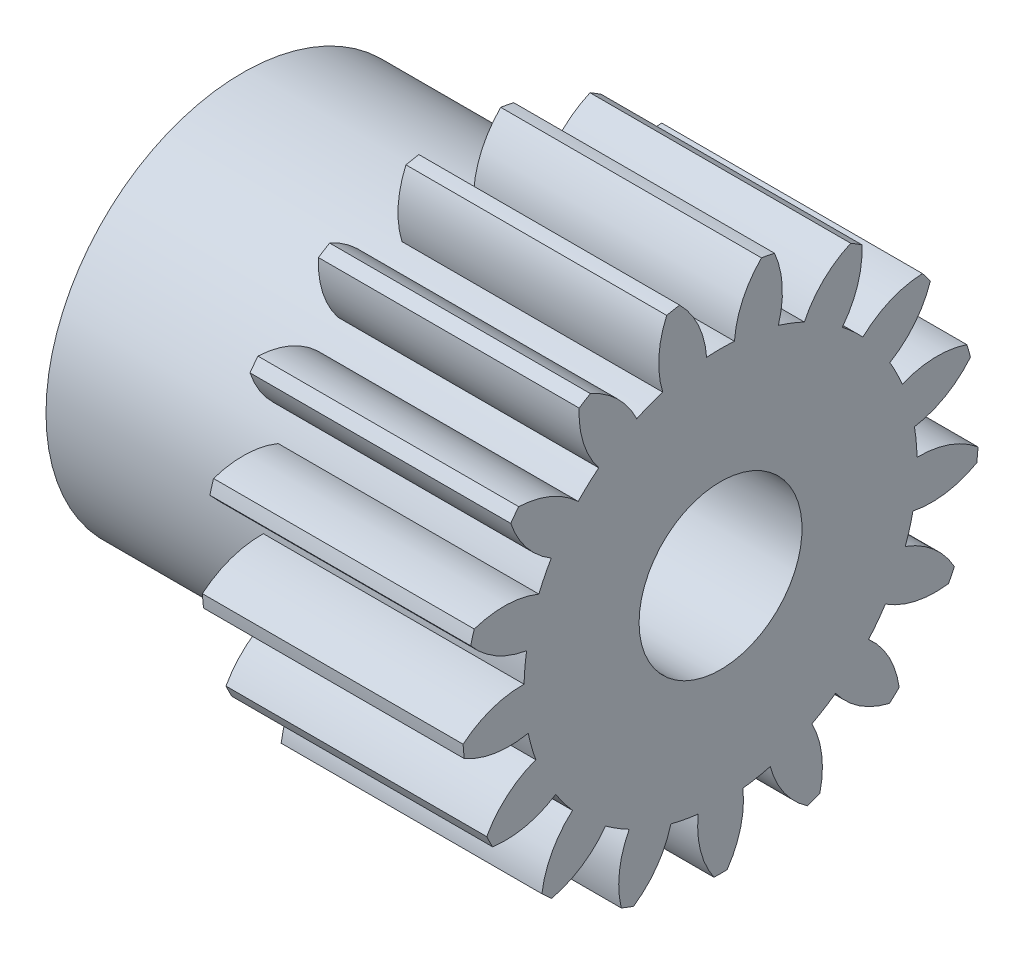
SolidWorks part; units mm, degrees
ref_plane "Plane1" through (0, 0, 0) normal (0, 0, 1) x (1, 0, 0)
ref_plane "Plane2" through (0, 0, 0) normal (0, 1, 0) x (1, 0, 0)
ref_plane "Plane3" through (0, 0, 0) normal (1, 0, 0) x (0, 0, -1)
sketch "HoldingSke" plane through (0, 0, 0) normal (0, 1, 0) x (1, 0, 0)
  line L0 (0, 0) -> (777.2845, -237.6397)
  line L1 (-15, 0) -> (100, 0) construction
  line L2 (0, 0) -> (-2.1039, 2.3779)
  line L3 (0, 0) -> (-11.863, 4.5341)
  line L4 (0, 0) -> (8.2586, 2.5249)
  line L5 (0, 0) -> (-13.0892, -4.8819)
  line L6 (0, 0) -> (-6.3167, -4.2619)
  line L7 (-2.1039, 2.3779) -> (0.9032, 16.0205)
  line L8 (-76.2, 54.61) -> (-71.1708, 54.61)
  line L9 (-71.009, 38.7566) -> (-53.1078, 45.2721)
  line L10 (-76.2, 71.12) -> (104.1128, 71.12)
  line L11 (0, 0) -> (-7.62, 0)
  line L12 (-76.2, 101.6) -> (-76.1716, 101.6)
  line L13 (24.9733, 27.94) -> (52.9518, 28.4284)
  line L14 (24.9733, 27.94) -> (25.0241, 27.9398)
  line L15 (24.9733, 27.94) -> (100.4021, 29.52)
  circle A0 centre (0, 0) radius 2.3813
  circle A1 centre (0, 0) radius 5.7436
  circle A2 centre (0, 0) radius 5.969
  circle A3 centre (0, 0) radius 2.3813
  dimension "MHD" = 11.4871
  dimension "Hub_dia" = 11.938
  dimension "Bore" = 4.7625
  dimension "MBD" = 4.7625
  dimension "Num_teeth" = 17
  dimension "Pitch" = 812.8
  dimension "Overall_len" = 13.97
  dimension "Show_teeth" = 17
  dimension "Thickness" = 7.62
  dimension "OAL" = 13.9701
  dimension "T_dim" = 5.0292
  dimension "Ap" = 20
  dimension "H" = 19.05
  dimension "Pitch_radius" = 180.3128
  dimension "Width" = 7.62
  dimension "Backlash" = 0.0284
  dimension "Addendum_fac" = 1
  dimension "Dedendum_fac" = 1.2
  dimension "Clearance_fac" = 0.2
  dimension "Dedendum_add" = 0.0508
sketch "BasProSke" plane through (0, 0, 0) normal (0, 1, 0) x (1, 0, 0)
  line L0 (-10, 0) -> (60, 0) construction
  line L1 (0, 0) -> (0, 7.5406)
  line L2 (0, 0) -> (7.62, 0)
  line L3 (7.62, 0) -> (7.62, 7.5406)
  line L4 (7.62, 7.5406) -> (0, 7.5406)
  dimension "Thickness" = 7.62
  dimension "Diameter" = 15.0812
revolve "Base-Revolve" add sketch "BasProSke" angle 360 about L0
sketch "TooCutSke" plane through (0, 0, 0) normal (1, 0, 0) x (0, 0, -1)
  line L1 (0, 0) -> (0, 107) construction
  line L2 (0, 0) -> (-0.6723, 6.7133) construction
  line L3 (0, 0) -> (-2.4705, 13.2161) construction
  line L4 (-0.6723, 6.7133) -> (-1.2353, 6.6081) construction
  arc A0 (0.4069, 5.7291) -> (-0.4069, 5.7291) centre (0, 0) ccw
  arc A1 (1.2182, 7.4673) -> (-1.2182, 7.4673) centre (0, 0) ccw
  circle A2 centre (0, 0) radius 6.7469 construction
  circle A3 centre (0, 0) radius 6.34 construction
  arc A4 (-0.4069, 5.7291) -> (-1.2182, 7.4673) centre (-3.0984, 5.5313) ccw
  arc A5 (1.2182, 7.4673) -> (0.4069, 5.7291) centre (3.0984, 5.5313) ccw
  dimension "Root_dia" = 11.4871
  dimension "Overcut_dia" = 15.132
  dimension "Pitch_dia" = 13.4937
  dimension "Base_dia" = 12.68
  dimension "Flank_rad" = 2.6987
  dimension "Half_ang" = 10.588
  dimension "Half_CT" = 0.5727
extrude "ToothCut" cut sketch "TooCutSke" along normal through all
fillet "Breaks" [suppressed] radius 0.0159
fillet "RootFillets" [suppressed] radius 0.2095
pattern_circular "TeethCuts" count 17 every 21.176 about axis through (-10, 0, 0) along (1, 0, 0) of "ToothCut", "RootFillets", "Breaks"
sketch "HubNeaOneSke" plane through (0, 0, 0) normal (-1, 0, 0) x (0, 0, 1)
  circle A0 centre (0, 0) radius 5.7436
  dimension "Diameter" = 11.4871
extrude "HubNearOne" add sketch "HubNeaOneSke" along normal blind 6.3501
sketch "HubNeaBotSke" plane through (0, 0, 0) normal (-1, 0, 0) x (0, 0, 1)
  circle A0 centre (0, 0) radius 5.7436
  dimension "Diameter" = 11.4871
extrude "HubNearBoth" [suppressed] add sketch "HubNeaBotSke" along normal blind 3.175
ref_plane "FarPln" through (7.62, 0, 0) normal (1, 0, 0) x (0, 0, -1)
sketch "HubFarSke" plane through (7.62, 0, 0) normal (1, 0, 0) x (0, 0, -1)
  circle A0 centre (0, 0) radius 5.7436
  dimension "Diameter" = 11.4871
extrude "HubFar" [suppressed] add sketch "HubFarSke" along normal blind 3.175
sketch "BorSke" plane through (0, 0, 0) normal (1, 0, 0) x (0, 0, -1)
  circle A0 centre (0, 0) radius 2.3813
  dimension "Diameter" = 4.7625
extrude "Bore" cut sketch "BorSke" along normal mid plane 27.9401
sketch "KeySke" plane through (0, 0, 0) normal (1, 0, 0) x (0, 0, -1)
  line L0 (-0.127, 0) -> (-0.127, 2.648)
  line L1 (-0.127, 2.648) -> (0.127, 2.648)
  line L2 (0.127, 2.648) -> (0.127, 0)
  line L3 (0, 0) -> (0, 34) construction
  line L4 (-0.127, 0) -> (0.127, 0)
  dimension "Offset" = 2.648
  dimension "Width" = 0.254
extrude "Keyway" [suppressed] cut sketch "KeySke" along normal mid plane 27.9401
pattern_circular "Keyway2" [suppressed] count 2 every 90 about axis through (-10, 0, 0) along (1, 0, 0)
equation "' \"Pitch@HoldingSke\" = 4"
equation "' \"Num_teeth@HoldingSke\" = 12"
equation "' \"Ap@HoldingSke\" =  20"
equation "' \"Ap@HoldingSke\" = 20"
equation "' \"Width@HoldingSke\" = 0.5"
equation "' \"Hub_dia@HoldingSke\"= 1"
equation "' \"Hub_dia@HoldingSke\" = 1"
equation "' \"Overall_len@HoldingSke\" = 1.0"
equation "' \"Bore@HoldingSke\" = 0.75"
equation "' \"T_dim@HoldingSke\" = 0.85"
equation "' \"Width@KeySke\" = 0.25"
equation "' \"Show_teeth@HoldingSke\" = 13"
equation "' \"Backlash@HoldingSke\" = 0.009"
equation "' \"Addendum_fac@HoldingSke\" = 1.0"
equation "' \"Dedendum_fac@HoldingSke\" = 1.25"
equation "' \"Dedendum_add@HoldingSke\" = 0.00005"
equation "' \"Clearance_fac@HoldingSke\" = 0.25"
equation "' \"Pitch@HoldingSke\" = 0.5"
equation "' \"Num_teeth@HoldingSke\" = 23"
equation "' \"Show_teeth@HoldingSke\" = 23"
equation "' \"Backlash@HoldingSke\" = 0.0375"
equation "\"Overcut_dia@TooCutSke\" = (\"Num_teeth@HoldingSke\" + 2 * \"Addendum_fac@HoldingSke\") / \"Pitch@HoldingSke\" + 0.002"
equation "\"Pitch_dia@TooCutSke\" = \"Num_teeth@HoldingSke\" / \"Pitch@HoldingSke\""
equation "\"Base_dia@TooCutSke\" = \"Num_teeth@HoldingSke\" / \"Pitch@HoldingSke\" * cos((\"Ap@HoldingSke\"  * 3.14159265 / 180))"
equation "\"Root_dia@TooCutSke\" = (\"Num_teeth@HoldingSke\" + 2) / \"Pitch@HoldingSke\" - 2 * (\"Addendum_fac@HoldingSke\" + \"Dedendum_fac@HoldingSke\") / \"Pitch@HoldingSke\" - \"Dedendum_add@HoldingSke\" * 2"
equation "\"Half_ang@TooCutSke\" = 180 / \"Num_teeth@HoldingSke\""
equation "\"Half_CT@TooCutSke\" = \"Num_teeth@HoldingSke\" / \"Pitch@HoldingSke\" * sin((3.14159265 / 2 / \"Num_teeth@HoldingSke\")) / 2 - 7 * \"Backlash@HoldingSke\" / 4"
equation "\"Flank_rad@TooCutSke\" = \"Num_teeth@HoldingSke\" / \"Pitch@HoldingSke\" / 5"
equation "\"Radius@RootFillets\" = \"Clearance_fac@HoldingSke\" / \"Pitch@HoldingSke\" + \"Dedendum_add@HoldingSke\""
equation "\"Break_rad@Breaks\" = 0.02 / \"Pitch@HoldingSke\""
equation "\"Thickness@HoldingSke\" = \"Width@HoldingSke\""
equation "\"OAL@HoldingSke\" = \"Thickness@HoldingSke\""
equation "\"MHD@HoldingSke\" = (\"Num_teeth@HoldingSke\" + 2) / \"Pitch@HoldingSke\" - 2 * (\"Addendum_fac@HoldingSke\" + \"Dedendum_fac@HoldingSke\")  / \"Pitch@HoldingSke\" - \"Dedendum_add@HoldingSke\" * 2"
equation "\"MBD@HoldingSke\" = (\"Num_teeth@HoldingSke\" + 2) / \"Pitch@HoldingSke\" - 2 * (\"Addendum_fac@HoldingSke\" + \"Dedendum_fac@HoldingSke\")  / \"Pitch@HoldingSke\" - \"Dedendum_add@HoldingSke\" * 2 - 0.002"
equation "\"MHD@HoldingSke\" = ((sgn( \"MHD@HoldingSke\" - \"Hub_dia@HoldingSke\" )-1)*( \"MHD@HoldingSke\" - \"Hub_dia@HoldingSke\" ))/-2+ \"Hub_dia@HoldingSke\""
equation "\"MBD@HoldingSke\" = ((sgn( \"MBD@HoldingSke\" - \"Bore@HoldingSke\" )-1)*( \"MBD@HoldingSke\" - \"Bore@HoldingSke\" ))/-2+ \"Bore@HoldingSke\""
equation "\"OAL@HoldingSke\" = ((sgn( \"OAL@HoldingSke\" - \"Overall_len@HoldingSke\" )+1)*( \"OAL@HoldingSke\" - \"Overall_len@HoldingSke\" ))/2 + \"Overall_len@HoldingSke\" + 0.000002"
equation "\"Num_teeth@TeethCuts\" = int( \"Show_teeth@HoldingSke\" ) + 1"
equation "\"Num_teeth@TeethCuts\" = ((sgn( \"Num_teeth@TeethCuts\" - \"Num_teeth@HoldingSke\" )-1)*( \"Num_teeth@TeethCuts\" - \"Num_teeth@HoldingSke\" ))/-2+ \"Num_teeth@HoldingSke\""
equation "\"Num_teeth@TeethCuts\" = ((sgn( \"Num_teeth@TeethCuts\" - 2.0)+1)*( \"Num_teeth@TeethCuts\" - 2.0))/2 +2.0"
equation "\"Angle@TeethCuts\" = 360.0 / \"Num_teeth@HoldingSke\""
equation "\"Diameter@BasProSke\" = (\"Num_teeth@HoldingSke\" + 2 * \"Addendum_fac@HoldingSke\") / \"Pitch@HoldingSke\""
equation "\"Thickness@BasProSke\"  = \"Thickness@HoldingSke\""
equation "' \"Fillet_rad@BasProSke\" =  \"Thickness@HoldingSke\" * 0.05"
equation "' \"Fillet_rad@BasProSke\" = \"Thickness@HoldingSke\" * 0.05"
equation "\"MHD@HoldingSke\" = ((sgn( \"MHD@HoldingSke\" - \"Root_dia@TooCutSke\" )-1)*( \"MHD@HoldingSke\" - \"Root_dia@TooCutSke\" ))/-2+ \"Root_dia@TooCutSke\""
equation "\"Diameter@HubNeaOneSke\" = \"MHD@HoldingSke\""
equation "\"Length@HubNearOne\" = \"OAL@HoldingSke\" - \"Thickness@BasProSke\""
equation "\"Diameter@HubNeaBotSke\" = \"MHD@HoldingSke\""
equation "\"Length@HubNearBoth\" = ( \"OAL@HoldingSke\" - \"Thickness@BasProSke\" ) / 2.0"
equation "\"Thickness@FarPln\" = \"Thickness@BasProSke\""
equation "\"Diameter@HubFarSke\" = \"MHD@HoldingSke\""
equation "\"Length@HubFar\" = ( \"OAL@HoldingSke\" - \"Thickness@BasProSke\" ) / 2.0"
equation "\"Diameter@BorSke\" = \"MBD@HoldingSke\""
equation "\"D1@Bore\" = \"OAL@HoldingSke\" * 2.0"
equation "\"D1@Keyway\" = \"OAL@HoldingSke\" * 2.0"
equation "\"Offset@KeySke\" = \"T_dim@HoldingSke\" - \"MBD@HoldingSke\" / 2.0"
